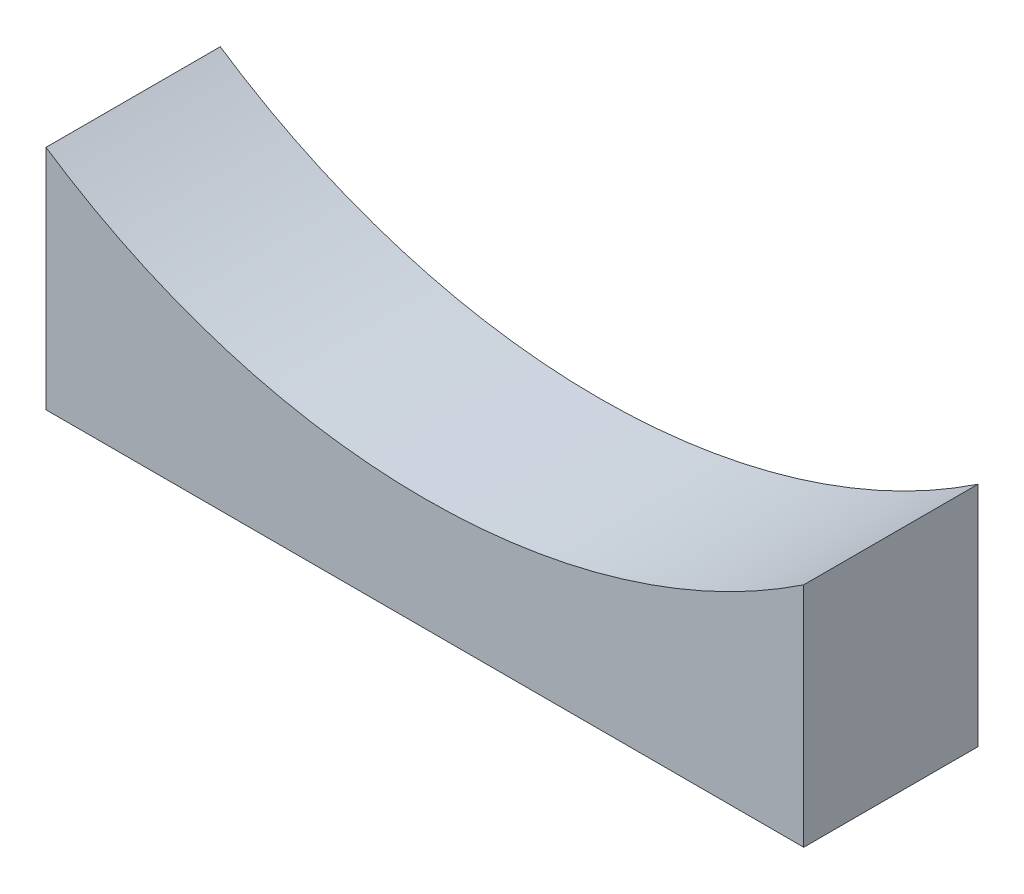
SolidWorks part; units mm, degrees
ref_plane "Front Plane" through (0, 0, 0) normal (0, 0, 1) x (1, 0, 0)
ref_plane "Top Plane" through (0, 0, 0) normal (0, 1, 0) x (1, 0, 0)
ref_plane "Right Plane" through (0, 0, 0) normal (1, 0, 0) x (0, 0, -1)
sketch "Sketch1" plane through (0, 0, 0) normal (0, 0, 1) x (1, 0, 0)
  line L0 (0, 0) -> (635, 0)
  line L1 (0, 190.5) -> (0, 0)
  line L2 (635, 190.5) -> (635, 0)
  arc A0 (0, 190.5) -> (635, 190.5) centre (317.5, 665.6905) ccw
  dimension "D1" = 190.5
  dimension "D2" = 1143
  dimension "D3" = 635
extrude "Boss-Extrude1" add sketch "Sketch1" along normal blind 146.05
